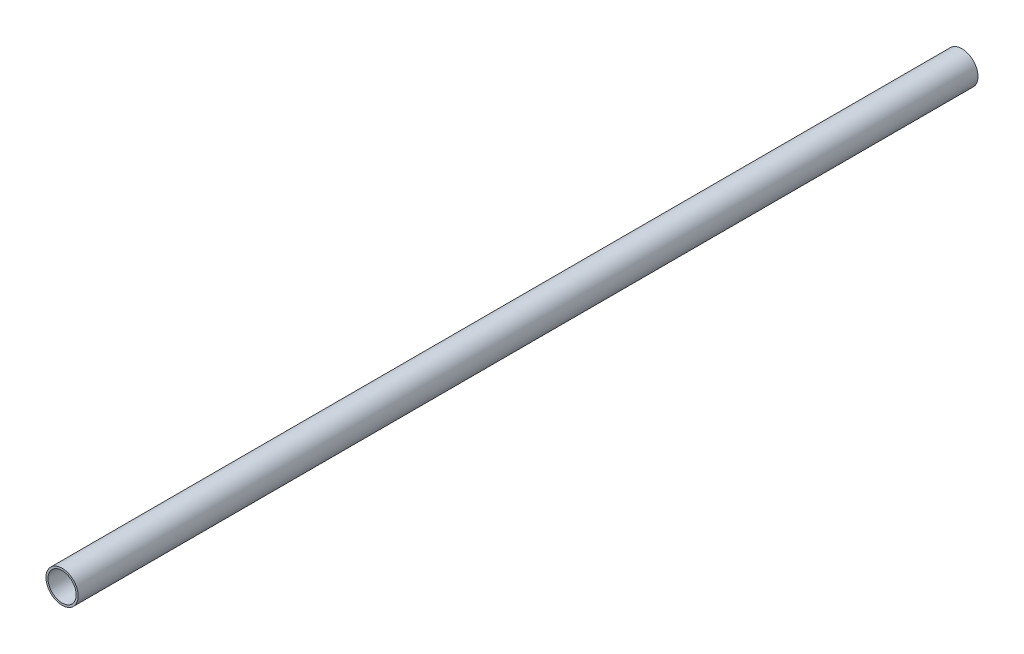
SolidWorks part; units mm, degrees
material "Thornel Mat VMA"
ref_plane "Front Plane" through (0, 0, 0) normal (0, 0, 1) x (1, 0, 0)
ref_plane "Top Plane" through (0, 0, 0) normal (0, 1, 0) x (1, 0, 0)
ref_plane "Right Plane" through (0, 0, 0) normal (1, 0, 0) x (0, 0, -1)
sketch "Sketch1" plane through (0, 0, 0) normal (1, 0, 0) x (0, 0, -1)
  line L0 (-47.7145, 0) -> (66.8488, 0) construction
  line L1 (-225.425, 7.0485) -> (225.425, 7.0485)
  line L2 (225.425, 7.0485) -> (225.425, 8.0645)
  line L3 (225.425, 8.0645) -> (-225.425, 8.0645)
  line L4 (-225.425, 8.0645) -> (-225.425, 7.0485)
  dimension "D1" = 8.0645
  dimension "D2" = 1.016
  dimension "D3" = 450.85
  dimension "D4" = 225.425
revolve "Revolve1" add sketch "Sketch1" angle 360 about L0
scale "Scale1" scale about centroid uniform scaling yes scale factor 0.6
